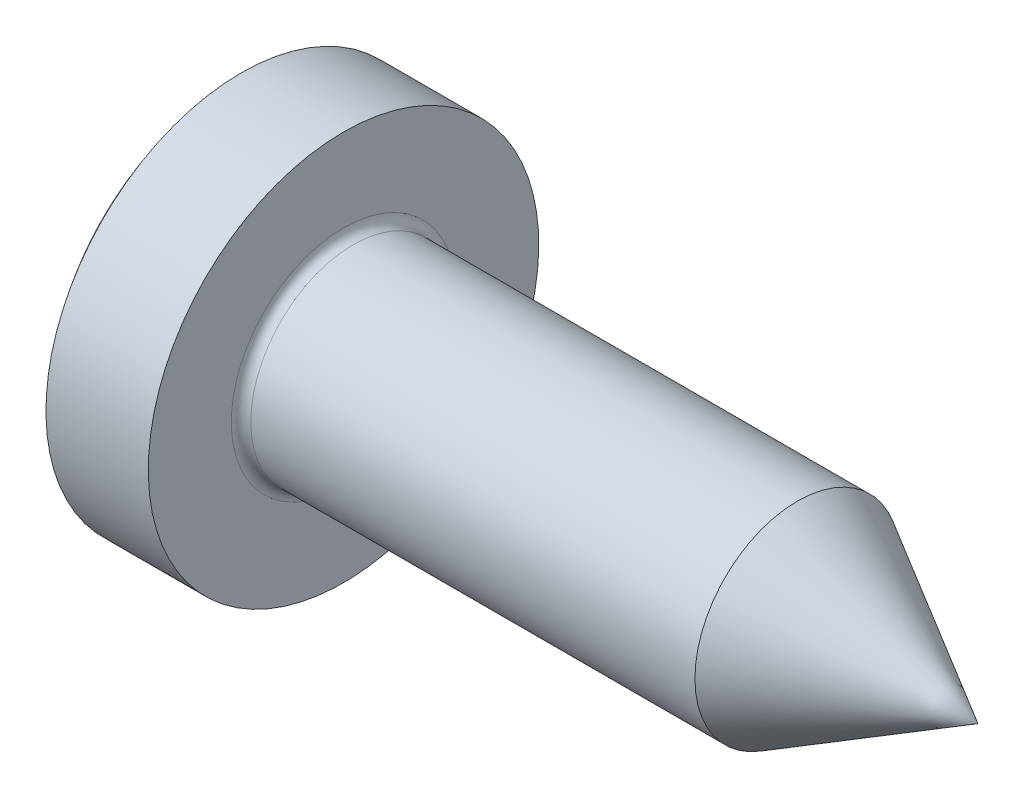
SolidWorks part; units mm, degrees
ref_plane "前视基准面" through (0, 0, 0) normal (0, 0, 1) x (1, 0, 0)
ref_plane "上视基准面" through (0, 0, 0) normal (0, 1, 0) x (1, 0, 0)
ref_plane "右视基准面" through (0, 0, 0) normal (1, 0, 0) x (0, 0, -1)
sketch "草图1" plane through (0, 0, 0) normal (0, 0, 1) x (1, 0, 0)
  line L0 (0, 0) -> (0, 8.1807) construction
  line L1 (0, 0) -> (12.8714, 0) construction
  line L2 (0, -4) -> (0, 4)
  line L3 (0, 4) -> (-3.1, 4)
  line L4 (-3.1, 4) -> (-3.1, -4)
  line L5 (0, -4) -> (-3.1, -4)
  line L6 (-3.1, 4) -> (-3.1, 5.4) construction
  line L7 (-3.1, 0) -> (-1.3, 0) construction
  line L8 (-3.1, 5.4) -> (-3.1, 5.6) construction
  line L9 (0, 4) -> (3.7, 4) construction
  arc A0 (-2.0973, 4) -> (-3.1, 2.1725) centre (3.0262, 0) ccw
  point P8 (-3.1, 0)
  point P12 (13, 0)
  point P13 (0, 2.1)
  point P14 (-3.1, 1.975)
  dimension "D1" = 4.345
  dimension "rf" = 6.5
  dimension "dk" = 8
  dimension "k" = 3.1
  dimension "l" = 13
  dimension "d" = 4.2
  dimension "A" = 3.95
  dimension "P" = 1.4
  dimension "t" = 1.8
  dimension "r" = 0.2
  dimension "y" = 3.7
sketch "草图2" plane through (0, 0, 0) normal (0, 0, 1) x (1, 0, 0)
  line L0 (0, -4) -> (0, 4) construction
  line L1 (0, 4) -> (-3.1, 4) construction
  line L2 (-3.1, 4) -> (-3.1, -4) construction
  line L4 (0, 0) -> (0, 4)
  line L5 (0, 4) -> (-2.0973, 4)
  line L6 (-3.1, 2.1725) -> (-3.1, 0)
  line L7 (0, 0) -> (-3.5506, 0) construction
  line L8 (-3.1, 0) -> (0, 0)
  arc A0 (-2.0973, 4) -> (-3.1, 2.1725) centre (3.0262, 0) ccw construction
  arc A1 (-2.0973, 4) -> (-3.1, 2.1725) centre (3.0262, 0) ccw
revolve "旋转1" add sketch "草图2" angle 360 about L7
sketch "草图3" plane through (0, 0, 0) normal (1, 0, 0) x (0, 0, -1)
  line L0 (0, 0) -> (0, 1.975) construction
  circle A0 centre (0, 0) radius 1.975 construction
  circle A1 centre (0, 0) radius 1.58 construction
  arc A2 (-0.4765, 1.6908) -> (0.4765, 1.6908) centre (0, 1.4334) cw
  arc A3 (0.4765, 1.6908) -> (1.226, 1.2581) centre (1.2026, 2.083) ccw
  arc A4 (1.7025, 0.4327) -> (1.7025, -0.4327) centre (2.4053, 0) ccw
  arc A5 (1.226, 1.2581) -> (1.7025, 0.4327) centre (1.2414, 0.7167) cw
  arc A6 (1.226, -1.2581) -> (0.4765, -1.6908) centre (1.2026, -2.083) ccw
  arc A7 (1.7025, -0.4327) -> (1.226, -1.2581) centre (1.2414, -0.7167) cw
  arc A8 (-0.4765, -1.6908) -> (-1.226, -1.2581) centre (-1.2026, -2.083) ccw
  arc A9 (0.4765, -1.6908) -> (-0.4765, -1.6908) centre (0, -1.4334) cw
  arc A10 (-1.7025, -0.4327) -> (-1.7025, 0.4327) centre (-2.4053, 0) ccw
  arc A11 (-1.226, -1.2581) -> (-1.7025, -0.4327) centre (-1.2414, -0.7167) cw
  arc A12 (-1.226, 1.2581) -> (-0.4765, 1.6908) centre (-1.2026, 2.083) ccw
  arc A13 (-1.7025, 0.4327) -> (-1.226, 1.2581) centre (-1.2414, 0.7167) cw
  dimension "D1" = 3.95
  dimension "D2" = 3.16
  dimension "R" = 0.8253
  dimension "D4" = 6
extrude "切除-拉伸1" cut sketch "草图3" against normal up to next
sketch "草图4" plane through (0, 0, 0) normal (0, 0, 1) x (1, 0, 0)
  line L0 (0, 0) -> (-3.1, 0) construction
  line L1 (0, 1.975) -> (-1.3, 1.975)
  line L2 (-1.3, 1.975) -> (-0.1597, 0)
  line L3 (-0.1597, 0) -> (0, 0)
  line L4 (0, 0) -> (0, 1.975)
  dimension "D1" = 1.8
  dimension "D2" = 60
revolve "旋转2" add sketch "草图4" angle 360 about L0
sketch "草图5" plane through (-3.1, 0, 0) normal (-1, 0, 0) x (0, 0, 1)
  circle A0 centre (0, 0) radius 2.1725
extrude "切除-拉伸2" cut sketch "草图5" against normal blind 5 draft 60
sketch "草图6" plane through (0, 0, 0) normal (0, 0, 1) x (1, 0, 0)
  line L0 (0, 2.1) -> (9.3, 2.1)
  line L1 (0, 0) -> (0, 2.1)
  line L2 (0, 0) -> (13, 0)
  line L3 (13, 0) -> (9.3, 2.1)
  line L4 (0, 0) -> (-2.742, 0) construction
  dimension "D1" = 3.7
revolve "旋转3" add sketch "草图6" angle 360 about L4
cosmetic thread "装饰螺纹线1" parameters "D2"=2.6845
fillet "圆角1" radius 0.2 1 edges at (0, 2.1, 0)
sketch "草图7" [suppressed] plane through (0, 0, 0) normal (0, 0, 1) x (1, 0, 0)
  line L0 (0, 0) -> (-4.2859, 0) construction
  line L1 (0, 1.45) -> (4.4, 1.45)
  line L2 (6.5, 0) -> (6.5, 1.1549)
  line L3 (6.5, 1.1549) -> (4.4, 1.45)
  line L4 (0, 1.45) -> (0, 0)
  line L5 (0, 0) -> (6.5, 0)
  dimension "D1" = 3.7
  dimension "D2" = 8
revolve "旋转4" [suppressed] add sketch "草图7" angle 360 about L0
cosmetic thread "装饰螺纹线2" [suppressed] parameters "D2"=2.6845
fillet "圆角2" [suppressed] radius 0.2
sketch "草图8" [suppressed] plane through (0, 0, 0) normal (0, 0, 1) x (1, 0, 0)
  line L0 (0, 0) -> (10.0279, 0) construction
  line L1 (0, -1.45) -> (0, 1.45)
  line L2 (0, 1.45) -> (4.4, 1.45)
  line L3 (4.4, 1.45) -> (6.3824, 0.2121)
  line L4 (4.4, -1.45) -> (6.3824, -0.2121)
  line L5 (0, -1.45) -> (4.4, -1.45)
  arc A0 (6.3824, 0.2121) -> (6.3824, -0.2121) centre (6.25, 0) cw
  point P11 (6.722, 0)
  dimension "D1" = 0.3621
  dimension "D2" = 3.7
sketch "草图9" [suppressed] plane through (0, 0, 0) normal (0, 0, 1) x (1, 0, 0)
  line L0 (0, -1.45) -> (0, 1.45) construction
  line L1 (0, 1.45) -> (4.4, 1.45) construction
  line L2 (4.4, 1.45) -> (6.3824, 0.2121) construction
  line L5 (0, 0) -> (0, 1.45)
  line L6 (0, 1.45) -> (4.4, 1.45)
  line L7 (4.4, 1.45) -> (6.3824, 0.2121)
  line L8 (0, 0) -> (-3.2712, 0) construction
  line L10 (6.5, 0) -> (0, 0)
  arc A0 (6.3824, -0.2121) -> (6.3824, 0.2121) centre (6.25, 0) ccw construction
  arc A1 (6.5, 0) -> (6.3824, 0.2121) centre (6.25, 0) ccw
revolve "旋转5" [suppressed] add sketch "草图9" angle 360 about L8
cosmetic thread "装饰螺纹线3" [suppressed] parameters "D2"=2.6845
fillet "圆角3" [suppressed] radius 0.2
